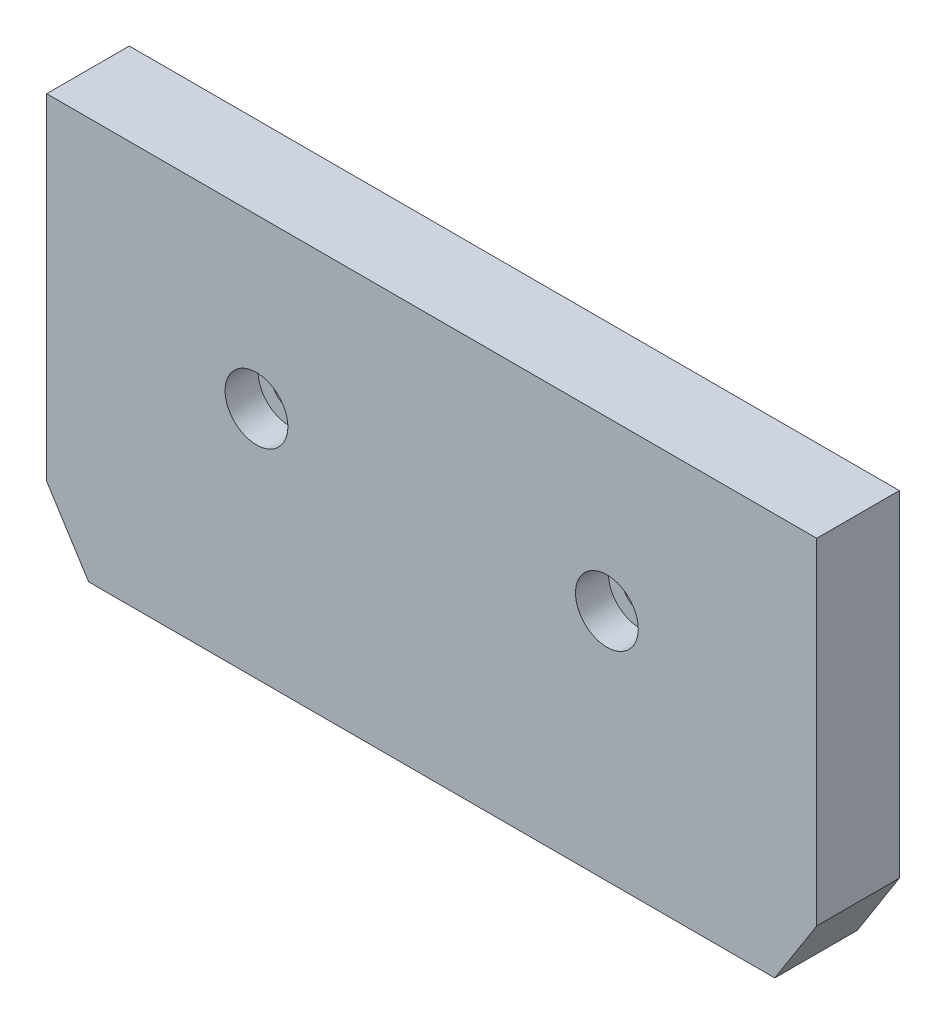
SolidWorks part; units mm, degrees
ref_plane "Front Plane" through (0, 0, 0) normal (0, 0, 1) x (1, 0, 0)
ref_plane "Top Plane" through (0, 0, 0) normal (0, 1, 0) x (1, 0, 0)
ref_plane "Right Plane" through (0, 0, 0) normal (1, 0, 0) x (0, 0, -1)
sketch "Sketch4" plane through (0, 0, 0) normal (0, 0, 1) x (1, 0, 0)
  line L0 (93.22, -13.9163) -> (98.3, -21.9163)
  line L1 (93.22, 26.7237) -> (186.44, 26.7237)
  line L2 (93.22, 26.7237) -> (93.22, -13.9163)
  line L3 (93.22, -13.9163) -> (186.44, -13.9163)
  line L4 (186.44, 26.7237) -> (186.44, -13.9163)
  line L5 (186.44, -13.9163) -> (181.36, -13.9163)
  line L7 (181.36, -21.9163) -> (139.83, -21.9163)
  line L8 (93.22, -13.9163) -> (98.3, -13.9163)
  line L10 (98.3, -21.9163) -> (139.83, -21.9163)
  line L11 (186.44, -13.9163) -> (181.36, -21.9163)
extrude "Boss-Extrude1" add sketch "Sketch4" along normal blind 10 contours L11 L3 L0 L10 L7 | L4 L1 L2 L3
sketch "Sketch5" plane through (0, 0, 10) normal (0, 0, 1) x (1, 0, 0)
  circle A0 centre (118.62, 6.4037) radius 3.8
  circle A1 centre (161.04, 6.4037) radius 3.8
  point P2 (163.0404, 2.7258)
extrude "Cut-Extrude1" cut sketch "Sketch5" against normal blind 3.9878
sketch "Sketch6" plane through (0, 0, 6.0122) normal (0, 0, 1) x (1, 0, 0)
  circle A1 centre (118.62, 6.4037) radius 2.05
extrude "Cut-Extrude2" cut sketch "Sketch6" against normal blind 7.7978
sketch "Sketch7" plane through (0, 0, 6.0122) normal (0, 0, 1) x (1, 0, 0)
  circle A1 centre (161.04, 6.4037) radius 2.05
extrude "Cut-Extrude5" cut sketch "Sketch7" against normal blind 7.7978 contours A1
